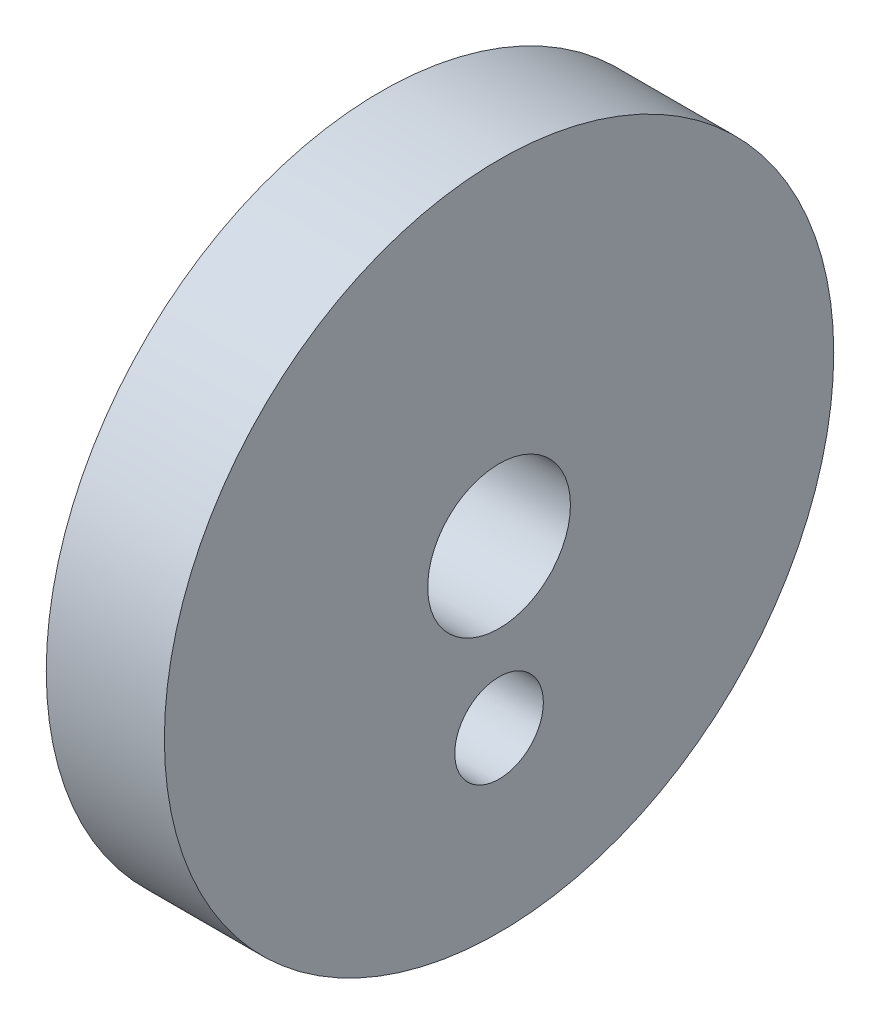
SolidWorks part; units mm, degrees
ref_plane "Front Plane" through (0, 0, 0) normal (0, 0, 1) x (1, 0, 0)
ref_plane "Top Plane" through (0, 0, 0) normal (0, 1, 0) x (1, 0, 0)
ref_plane "Right Plane" through (0, 0, 0) normal (1, 0, 0) x (0, 0, -1)
sketch "Sketch1" plane through (0, 0, 0) normal (1, 0, 0) x (0, 0, -1)
  circle A0 centre (0, 0) radius 34
extrude "Boss-Extrude1" add sketch "Sketch1" along normal blind 12 contours A0
hole_wizard "M13 Clearance Hole1" positions "Sketch5" profile "Sketch3" hole size "M13" standard "ISO"
sketch "Sketch5" plane through (12, 0, 0) normal (1, 0, 0) x (0, 0, -1)
  point P0 (0, 0)
sketch "Sketch3" plane through (12, 0, 0) normal (0, 1, 0) x (0, 0, -1)
  line L0 (0, 0) -> (0, 34.3562)
  line L1 (0, 34.3562) -> (7.25, 30)
  line L2 (7.25, 30) -> (7.25, 0)
  line L5 (7.25, 0) -> (0, 0)
  line L10 (0, 34.3562) -> (-7.25, 30) construction
  line L11 (0, -6.35) -> (0, 107.95) construction
  dimension "Hole Dia." = 14.5
  dimension "Hole Depth" = 30
  dimension "Drill Angle" = 118
sketch "Sketch6" plane through (12, 0, 0) normal (1, 0, 0) x (0, 0, -1)
  line L0 (0, -7.25) -> (0, -34) construction
  circle A0 centre (0, 0) radius 7.25 construction
  circle A1 centre (0, 0) radius 34 construction
  point P9 (0, -16)
  dimension "D1" = 16
hole_wizard "M8 Clearance Hole1" positions "Sketch6" profile "Sketch7" hole size "M8" standard "ANSI Metric"
sketch "Sketch7" plane through (12, -16, 0) normal (0, 1, 0) x (0, 0, -1)
  line L0 (0, 0) -> (0, 32.7039)
  line L1 (0, 32.7039) -> (4.5, 30)
  line L2 (4.5, 30) -> (4.5, 0)
  line L5 (4.5, 0) -> (0, 0)
  line L10 (0, 32.7039) -> (-4.5, 30) construction
  line L11 (0, -6.35) -> (0, 107.95) construction
  dimension "Hole Dia." = 9
  dimension "Hole Depth" = 30
  dimension "Drill Angle" = 118
